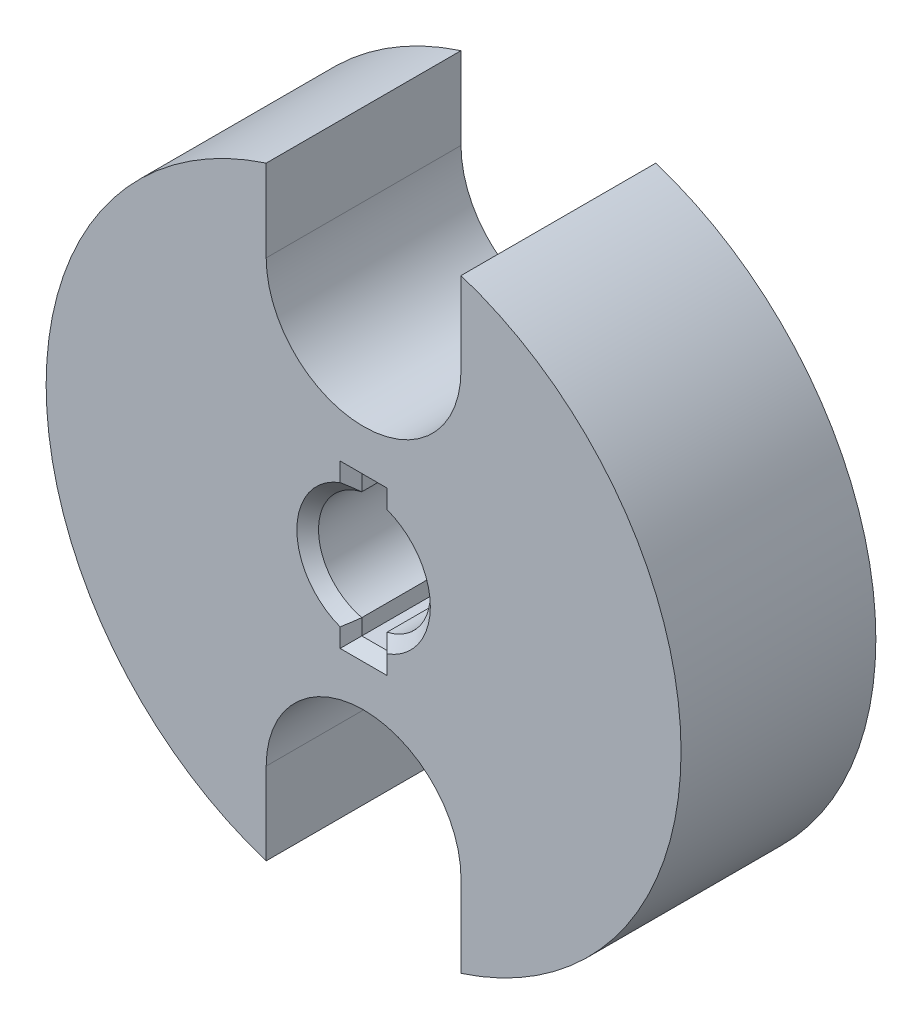
SolidWorks part; units mm, degrees
ref_plane "Front Plane" through (0, 0, 0) normal (0, 0, 1) x (1, 0, 0)
ref_plane "Top Plane" through (0, 0, 0) normal (0, 1, 0) x (1, 0, 0)
ref_plane "Right Plane" through (0, 0, 0) normal (1, 0, 0) x (0, 0, -1)
sketch "Sketch1" plane through (0, 0, 0) normal (0, 0, 1) x (1, 0, 0)
  line L1 (-6.75, 25) -> (6.75, 25)
  line L2 (-6.75, 25) -> (-6.75, -25)
  line L3 (-6.75, -25) -> (6.75, -25)
  line L4 (6.75, 25) -> (6.75, -25)
  line L5 (-6.75, 25) -> (6.75, -25) construction
  line L6 (-6.75, -25) -> (6.75, 25) construction
  line L7 (-0.875, 4.875) -> (0.875, 4.875)
  line L8 (-0.875, 4.875) -> (-0.875, -4.875)
  line L9 (-0.875, -4.875) -> (0.875, -4.875)
  line L10 (0.875, 4.875) -> (0.875, -4.875)
  line L11 (-0.875, 4.875) -> (0.875, -4.875) construction
  line L12 (-0.875, -4.875) -> (0.875, 4.875) construction
  circle A0 centre (0, 0) radius 22
  circle A1 centre (0, 15.25) radius 6.75
  circle A2 centre (0, -15.25) radius 6.75
  circle A3 centre (0, 0) radius 3.875
  dimension "D1" = 44
  dimension "D2" = 13.5
  dimension "D3" = 13.5
  dimension "D6" = 7.75
  dimension "D4" = 13.5
  dimension "D5" = 50
  dimension "D7" = 9.75
  dimension "D8" = 1.75
extrude "Boss-Extrude1" add sketch "Sketch1" along normal blind 13.5 contours L2 A0 | L4 A0 | A2 L4 A1 L2 A3 L8 L7 L10 L9
chamfer "Chamfer1" distance 0.75 angle 45 8 edges at (0.875, -4.325, 0) (0, -4.875, 0) (-0.875, -4.325, 0) (-3.875, 0, 0) (-0.875, 4.325, 0) (0, 4.875, 0) (0.875, 4.325, 0) (3.875, 0, 0)
chamfer "Chamfer2" distance 0.75 angle 45 8 edges at (-0.875, -4.325, 13.5) (0, -4.875, 13.5) (0.875, -4.325, 13.5) (3.875, 0, 13.5) (0.875, 4.325, 13.5) (0, 4.875, 13.5) (-0.875, 4.325, 13.5) (-3.875, 0, 13.5)
scale "Scale1" scale about centroid uniform scaling yes scale factor 0.9
